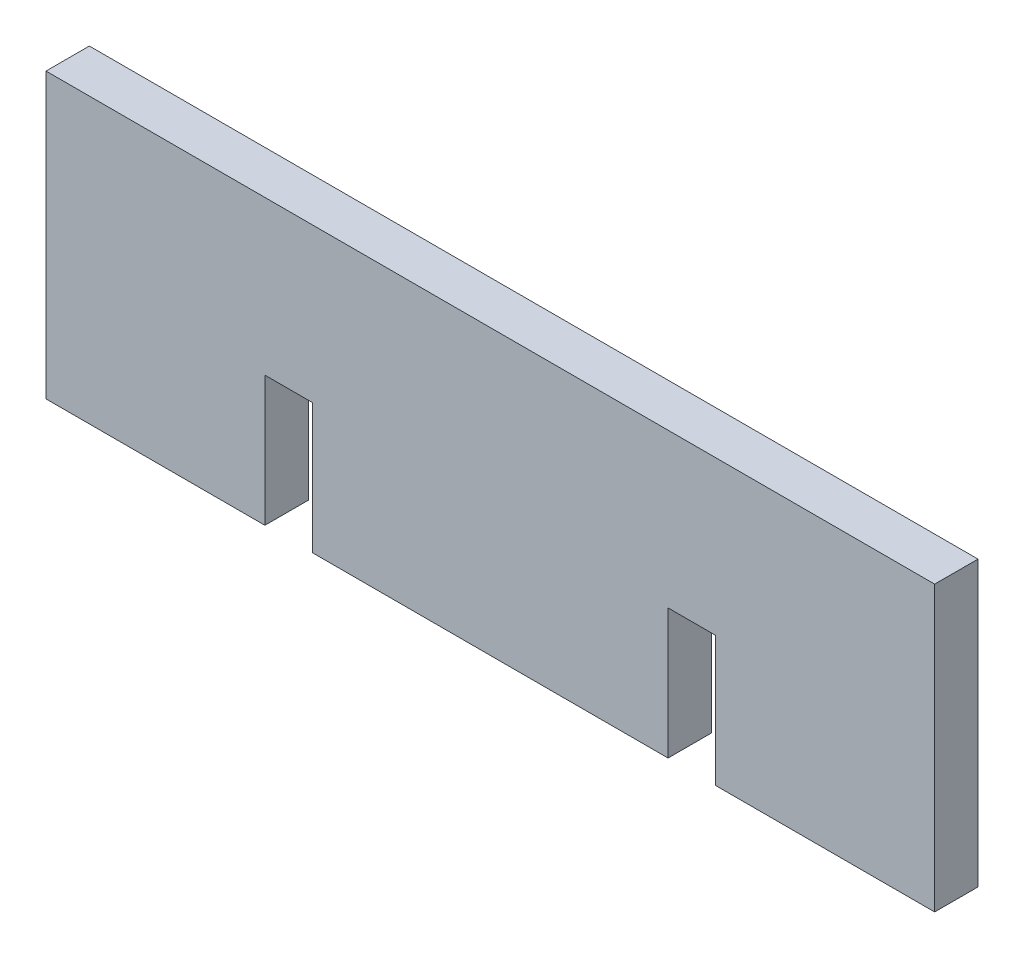
SolidWorks part; units mm, degrees
ref_plane "前视基准面" through (0, 0, 0) normal (0, 0, 1) x (1, 0, 0)
ref_plane "上视基准面" through (0, 0, 0) normal (0, 1, 0) x (1, 0, 0)
ref_plane "右视基准面" through (0, 0, 0) normal (1, 0, 0) x (0, 0, -1)
sketch "草图1" plane through (0, 0, 0) normal (0, 0, 1) x (1, 0, 0)
  line L0 (-41, -32.75) -> (41, -32.75)
  line L1 (-102.5, 32.75) -> (102.5, 32.75)
  line L2 (-102.5, 32.75) -> (-102.5, -32.75)
  line L3 (-102.5, -32.75) -> (-52, -32.75)
  line L4 (102.5, 32.75) -> (102.5, -32.75)
  line L5 (-102.5, 32.75) -> (102.5, -32.75) construction
  line L6 (-102.5, -32.75) -> (102.5, 32.75) construction
  line L7 (41, -32.75) -> (41, -2.75)
  line L8 (41, -2.75) -> (52, -2.75)
  line L9 (52, -2.75) -> (52, -32.75)
  line L10 (-41, -32.75) -> (-41, -2.75)
  line L11 (-41, -2.75) -> (-52, -2.75)
  line L12 (-52, -2.75) -> (-52, -32.75)
  line L13 (-41, -32.75) -> (41, -32.75)
  line L14 (52, -32.75) -> (102.5, -32.75)
  point P0 (0, 0)
  point P9 (0, -32.75)
  dimension "D1" = 205
  dimension "D2" = 65.5
extrude "凸台-拉伸1" add sketch "草图1" along normal blind 10 contours L9 L14 L4 L1 L2 L3 L12 L11 L10 L0 L7 L8
